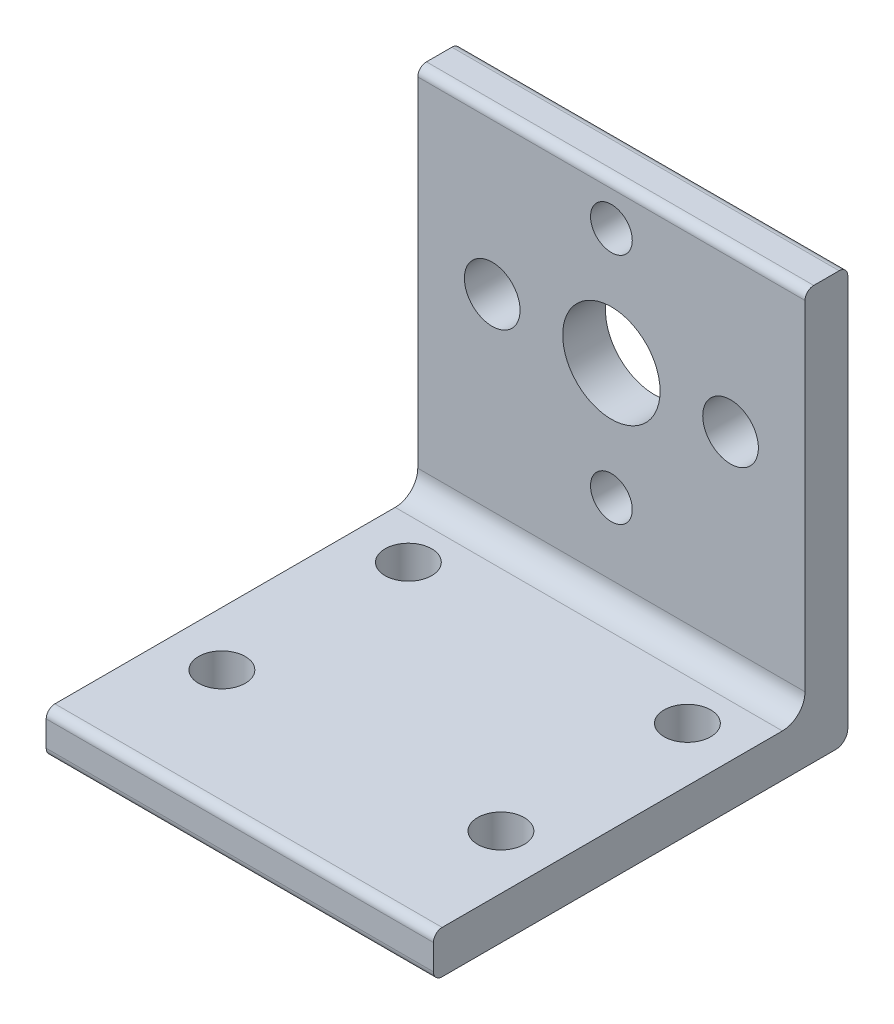
SolidWorks part; units mm, degrees
material "6061-T6 (SS)"
ref_plane "Front Plane" through (0, 0, 0) normal (0, 0, 1) x (1, 0, 0)
ref_plane "Top Plane" through (0, 0, 0) normal (0, 1, 0) x (1, 0, 0)
ref_plane "Right Plane" through (0, 0, 0) normal (1, 0, 0) x (0, 0, -1)
sketch "Sketch1" plane through (0, 0, 0) normal (1, 0, 0) x (0, 0, -1)
  line L0 (0, 0) -> (0, -30.1498)
  line L1 (0, -30.1498) -> (-30.2514, -30.1498)
  line L2 (-30.2514, -30.1498) -> (-30.2514, -27.0256)
  line L3 (-30.2514, -27.0256) -> (-3.1242, -27.0256)
  line L4 (-3.1242, -27.0256) -> (-3.1242, 0)
  line L5 (-3.1242, 0) -> (0, 0)
  dimension "D1" = 30.2514
  dimension "D2" = 30.1498
  dimension "D3" = 3.1242
  dimension "D4" = 3.1242
extrude "Boss-Extrude1" add sketch "Sketch1" along normal blind 28.2702
sketch "Sketch2" plane through (0, 0, 3.1242) normal (0, 0, 1) x (1, 0, 0)
  line L0 (14.1351, -3.1496) -> (14.1351, -20.1676) construction
  line L2 (28.2702, 0) -> (0, 0) construction
  line L3 (5.4356, -11.6586) -> (22.8346, -11.6586) construction
  line L6 (0, -11.6586) -> (28.2702, -11.6586) construction
  line L9 (0, 0) -> (0, -27.0256) construction
  line L10 (28.2702, 0) -> (28.2702, -27.0256) construction
  circle A0 centre (14.1351, -11.6586) radius 3.556
  circle A1 centre (14.1351, -3.1496) radius 1.524
  circle A2 centre (5.4356, -11.6586) radius 2.032
  circle A3 centre (22.8346, -11.6586) radius 2.032
  circle A4 centre (14.1351, -20.1676) radius 1.524
  point P0 (14.1351, -11.6586)
  dimension "D1" = 7.112
  dimension "D2" = 3.048
  dimension "D3" = 11.6586
  dimension "D7" = 4.064
  dimension "D4" = 17.399
  dimension "D5" = 17.018
extrude "Motor_Mount_holes" cut sketch "Sketch2" against normal through all
sketch "Sketch3" plane through (0, -27.0256, 0) normal (0, 1, 0) x (1, 0, 0)
  line L0 (14.1351, -3.1242) -> (14.1351, -30.2514) construction
  line L1 (28.2702, -3.1242) -> (0, -3.1242) construction
  line L2 (28.2702, -30.2514) -> (0, -30.2514) construction
  line L3 (28.2702, 0) -> (0, 0) construction
  line L5 (0, -14.5669) -> (28.2702, -14.5669) construction
  circle A0 centre (24.3205, -7.7597) radius 1.7018
  circle A1 centre (3.9497, -7.7597) radius 1.7018
  circle A2 centre (3.9497, -21.3741) radius 1.7018
  circle A3 centre (24.3205, -21.3741) radius 1.7018
  dimension "D1" = 3.4036
  dimension "D2" = 20.3708
  dimension "D3" = 13.6144
  dimension "D4" = 7.7597
extrude "Plate_Mount_Holes" cut sketch "Sketch3" against normal through all
fillet "Fillet1" radius 1.651 1 edges at (14.1351, -27.0256, 3.1242)
fillet "Fillet2" radius 0.889 1 edges at (14.1351, -30.1498, 0)
fillet "Fillet3" radius 0.635 4 edges at (14.1351, -30.1498, 30.2514) (14.1351, -27.0256, 30.2514) (14.1351, 0, 0) (14.1351, 0, 3.1242)
